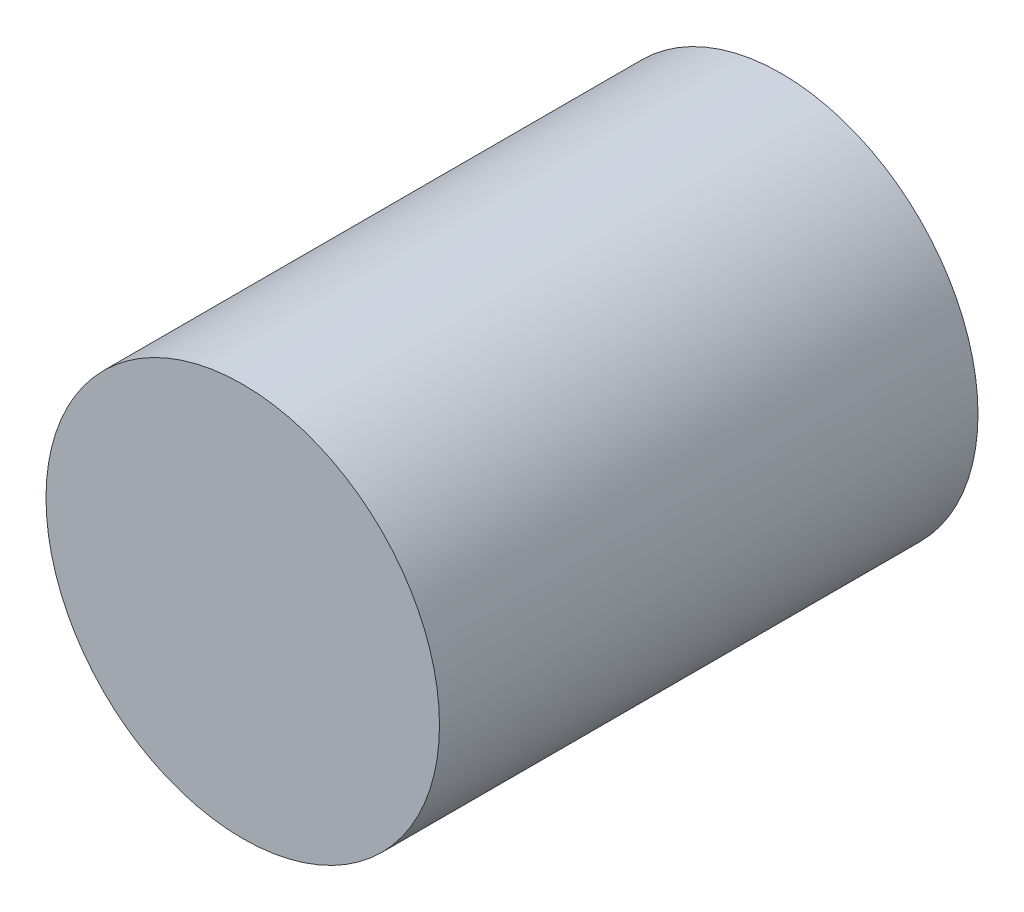
SolidWorks part; units mm, degrees
ref_plane "Front Plane" through (0, 0, 0) normal (0, 0, 1) x (1, 0, 0)
ref_plane "Top Plane" through (0, 0, 0) normal (0, 1, 0) x (1, 0, 0)
ref_plane "Right Plane" through (0, 0, 0) normal (1, 0, 0) x (0, 0, -1)
sketch "Sketch2" plane through (0, 0, 0) normal (1, 0, 0) x (0, 0, -1)
  line L0 (0, 0) -> (0, 6.9596)
  line L1 (0, 6.9596) -> (19.05, 6.9596)
  line L2 (19.05, 6.9596) -> (19.05, 0)
  line L3 (19.05, 0) -> (0, 0)
  line L4 (0, 0) -> (29.1332, 0) construction
  dimension "D1" = 13.9192
  dimension "D2" = 19.05
revolve "Revolve1" add sketch "Sketch2" angle 360 about L4
